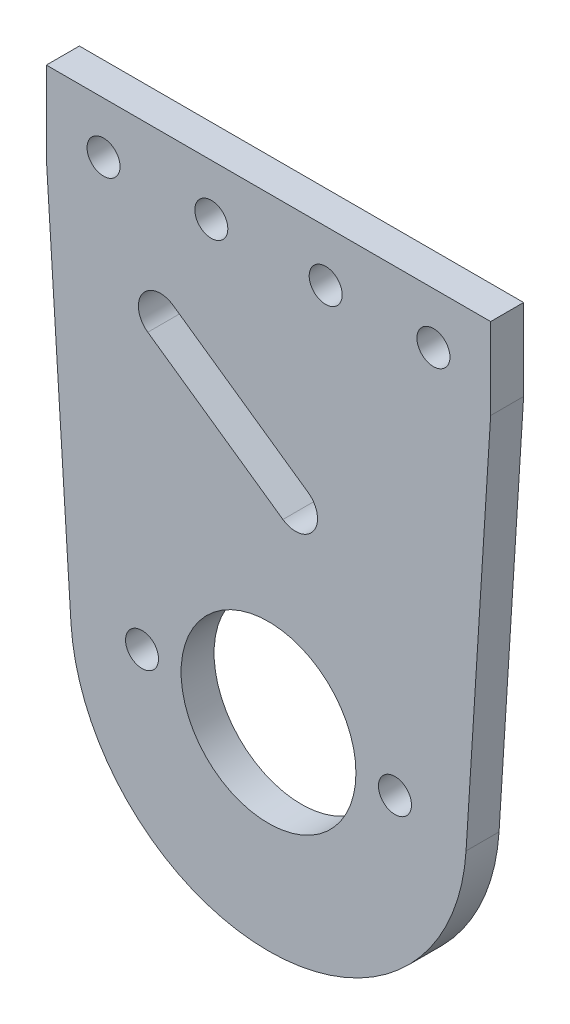
SolidWorks part; units mm, degrees
material "Acrylic (Medium-high impact)"
ref_plane "Front Plane" through (0, 0, 0) normal (0, 0, 1) x (1, 0, 0)
ref_plane "Top Plane" through (0, 0, 0) normal (0, 1, 0) x (1, 0, 0)
ref_plane "Right Plane" through (0, 0, 0) normal (1, 0, 0) x (0, 0, -1)
sketch "Sketch1" plane through (0, 0, 0) normal (0, 0, 1) x (1, 0, 0)
  line L0 (0, 83.4741) -> (0, 41.6741) construction
  line L1 (0, 41.6741) -> (20.2, 41.6741)
  line L2 (20.2, 41.6741) -> (20.2, 83.4741) construction
  line L3 (20.2, 83.4741) -> (0, 83.4741) construction
  line L4 (10.1, 83.4741) -> (10.1, 41.6741) construction
  line L5 (10.1, 62.5741) -> (20.2, 62.5741) construction
  line L6 (-20.2, 83.4741) -> (-20.2, 41.6741) construction
  line L7 (-20.2, 41.6741) -> (0, 41.6741)
  line L8 (0, 0) -> (0, 90.8741) construction
  line L9 (0, 83.4741) -> (-20.2, 83.4741) construction
  line L10 (-10.1, 83.4741) -> (-10.1, 41.6741) construction
  line L11 (-20.2, 62.5741) -> (-10.1, 62.5741) construction
  line L12 (-20.2, 34.2741) -> (-17.9642, -1.1343)
  line L13 (20.2, 34.2741) -> (17.9642, -1.1343)
  line L14 (-20.2, 34.2741) -> (20.2, 34.2741) construction
  line L15 (-20.2, 41.6741) -> (-20.2, 34.2741)
  line L16 (20.2, 41.6741) -> (20.2, 34.2741)
  circle A0 centre (10.1, 73.3741) radius 6.5 construction
  arc A1 (-17.9642, -1.1343) -> (17.9642, -1.1343) centre (0, 0) cw construction
  circle A2 centre (0, 0) radius 7.95
  arc A3 (-17.9642, -1.1343) -> (17.9642, -1.1343) centre (0, 0) ccw
  circle A4 centre (5.2, 88.1241) radius 1.5 construction
  circle A5 centre (15, 88.1241) radius 1.5 construction
  circle A6 centre (-10.1, 51.7741) radius 6.5 construction
  circle A7 centre (-15, 88.1241) radius 1.5 construction
  circle A8 centre (-5.2, 88.1241) radius 1.5 construction
  circle A9 centre (-15, 37.0241) radius 1.5
  circle A10 centre (-5.2, 37.0241) radius 1.5
  circle A11 centre (0, 0) radius 52.75 construction
  circle A12 centre (5.2, 37.0241) radius 1.5
  circle A13 centre (15, 37.0241) radius 1.5
  dimension "D1" = 15.9
  dimension "D2" = 51.1
  dimension "D10" = 10.1
  dimension "D3" = 18
  dimension "D14" = 105.5
  dimension "D16" = 9.8
  dimension "D6" = 10.1
  dimension "D7" = 13
  dimension "D8" = 3
  dimension "D9" = 20.2
  dimension "D11" = 41.8
  dimension "D12" = 9.8
  dimension "D18" = 7.4
  dimension "D19" = 7.4
extrude "Main Body Link B2" add sketch "Sketch1" along normal blind 3
sketch "Sketch2" plane through (0, 0, 3) normal (0, 0, 1) x (1, 0, 0)
  line L0 (0, -7.95) -> (0, 7.95) construction
  circle A0 centre (-11.5, 0) radius 1.5
  circle A1 centre (11.5, 0) radius 1.5
  circle A2 centre (0, 0) radius 7.95 construction
  dimension "D1" = 3
  dimension "D2" = 11.5
extrude "Cut-Extrude1" cut sketch "Sketch2" against normal up to next
sketch "Sketch3" plane through (0, 0, 3) normal (0, 0, 1) x (1, 0, 0)
  line L0 (0, 0) -> (0, 20) construction
  line L1 (-9.8298, 26.8829) -> (2.4575, 18.2793) construction
  line L2 (-8.6827, 28.5212) -> (3.6046, 19.9176)
  line L3 (-10.977, 25.2446) -> (1.3103, 16.641)
  arc A0 (-8.6827, 28.5212) -> (-10.977, 25.2446) centre (-9.8298, 26.8829) ccw
  arc A1 (1.3103, 16.641) -> (3.6046, 19.9176) centre (2.4575, 18.2793) ccw
  dimension "D5" = 4
  dimension "D1" = 55
  dimension "D2" = 3
  dimension "D3" = 12
  dimension "D4" = 20
extrude "Cut-Extrude2" cut sketch "Sketch3" against normal through all
equation "\"D1@Sketch1\"=16.00mm-\"radii_fit@Parameters@Parameters.SLDPRT\""
equation "\"D14@Sketch1\"=\"CenterDist2@Parameters@Parameters.SLDPRT\"*2"
